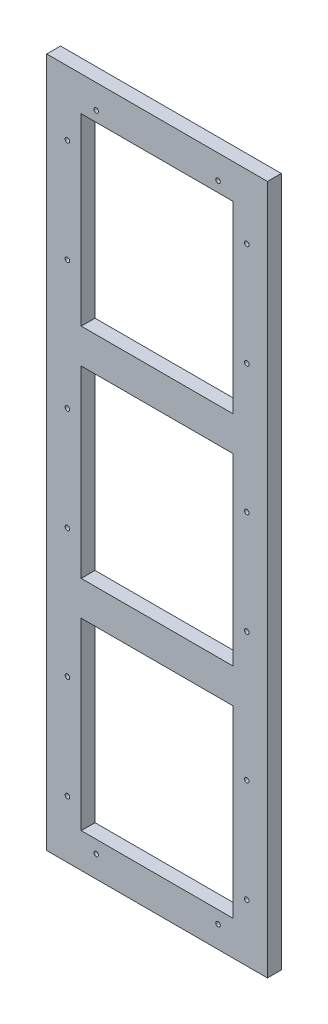
SolidWorks part; units mm, degrees
material "Alumina"
ref_plane "Front Plane" through (0, 0, 0) normal (0, 0, 1) x (1, 0, 0)
ref_plane "Top Plane" through (0, 0, 0) normal (0, 1, 0) x (1, 0, 0)
ref_plane "Right Plane" through (0, 0, 0) normal (1, 0, 0) x (0, 0, -1)
sketch "Sketch1" plane through (0, 0, 0) normal (0, 0, 1) x (1, 0, 0)
  line L0 (33, 141) -> (33, 61)
  line L9 (-48, -144) -> (48, -144)
  line L10 (-48, -144) -> (-48, 156)
  line L11 (-48, 156) -> (48, 156)
  line L12 (48, -144) -> (48, 156)
  line L14 (0, 0) -> (0, 46) construction
  line L15 (-33, -129) -> (33, -129)
  line L17 (-33, 141) -> (33, 141)
  line L19 (-33, 46) -> (-33, -34)
  line L20 (-33, -49) -> (-33, -129)
  line L21 (-33, 61) -> (33, 61)
  line L23 (-33, 46) -> (33, 46)
  line L25 (-33, -34) -> (33, -34)
  line L27 (-33, -49) -> (33, -49)
  line L33 (33, 46) -> (33, -34)
  line L34 (-33, 61) -> (-33, 141)
  line L36 (33, -49) -> (33, -129)
  dimension "D1" = 96
  dimension "D2" = 15
  dimension "D3" = 66
  dimension "D4" = 80
  dimension "D5" = 15
  dimension "D6" = 80
  dimension "D7" = 15
  dimension "D8" = 80
  dimension "D9" = 46
  dimension "D10" = 15
  dimension "D12" = 15
extrude "Boss-Extrude1" add sketch "Sketch1" along normal blind 6
sketch "Sketch3" plane through (0, 0, 6) normal (0, 0, 1) x (1, 0, 0)
  line L0 (48, 156) -> (-48, 156) construction
  line L1 (-48, 156) -> (-48, -144) construction
  line L2 (-39, 128) -> (39, 128) construction
  line L4 (-39, 128) -> (-39, 83) construction
  line L5 (-39, 128) -> (-39, 27) construction
  circle A0 centre (-39, 128) radius 1
  circle A26 centre (-39, 27) radius 1
  circle A27 centre (39, 128) radius 1
  circle A28 centre (39, 83) radius 1
  circle A29 centre (-39, 83) radius 1
  circle A30 centre (39, 27) radius 1
  circle A31 centre (39, -18) radius 1
  circle A32 centre (-39, -18) radius 1
  circle A33 centre (-39, -74) radius 1
  circle A34 centre (39, -74) radius 1
  circle A35 centre (39, -119) radius 1
  circle A36 centre (-39, -119) radius 1
  dimension "D1" = 28
  dimension "D12" = 2
  dimension "D13" = 45
  dimension "D14" = 9
  dimension "D2" = 78
  dimension "D16" = 101
  dimension "D4" = 2
  dimension "D5" = 2
  dimension "D15" = 3
extrude "Cut-Extrude6" cut sketch "Sketch3" against normal blind 10
ref_plane "Plane1" through (0, 6, 0) normal (0, 1, 0) x (1, 0, 0)
sketch "Sketch5" plane through (0, 0, 6) normal (0, 0, 1) x (1, 0, 0)
  line L0 (-26.5, 145.5) -> (26.5, 145.5) construction
  line L1 (26.5, 145.5) -> (26.5, -134.5) construction
  line L2 (26.5, -134.5) -> (-26.5, -134.5) construction
  line L3 (-26.5, -134.5) -> (-26.5, 145.5) construction
  line L4 (48, 156) -> (-48, 156) construction
  line L5 (-48, -144) -> (48, -144) construction
  line L6 (48, -144) -> (48, 156) construction
  line L7 (-48, 156) -> (-48, -144) construction
  circle A0 centre (-26.5, -134.5) radius 1
  circle A1 centre (26.5, -134.5) radius 1
  circle A2 centre (-26.5, 145.5) radius 1
  circle A3 centre (26.5, 145.5) radius 1
  dimension "D5" = 2
  dimension "D6" = 2
  dimension "D7" = 2
  dimension "D8" = 2
  dimension "D1" = 10.5
  dimension "D2" = 9.5
  dimension "D3" = 21.5
  dimension "D4" = 21.5
extrude "Cut-Extrude9" cut sketch "Sketch5" against normal blind 10
